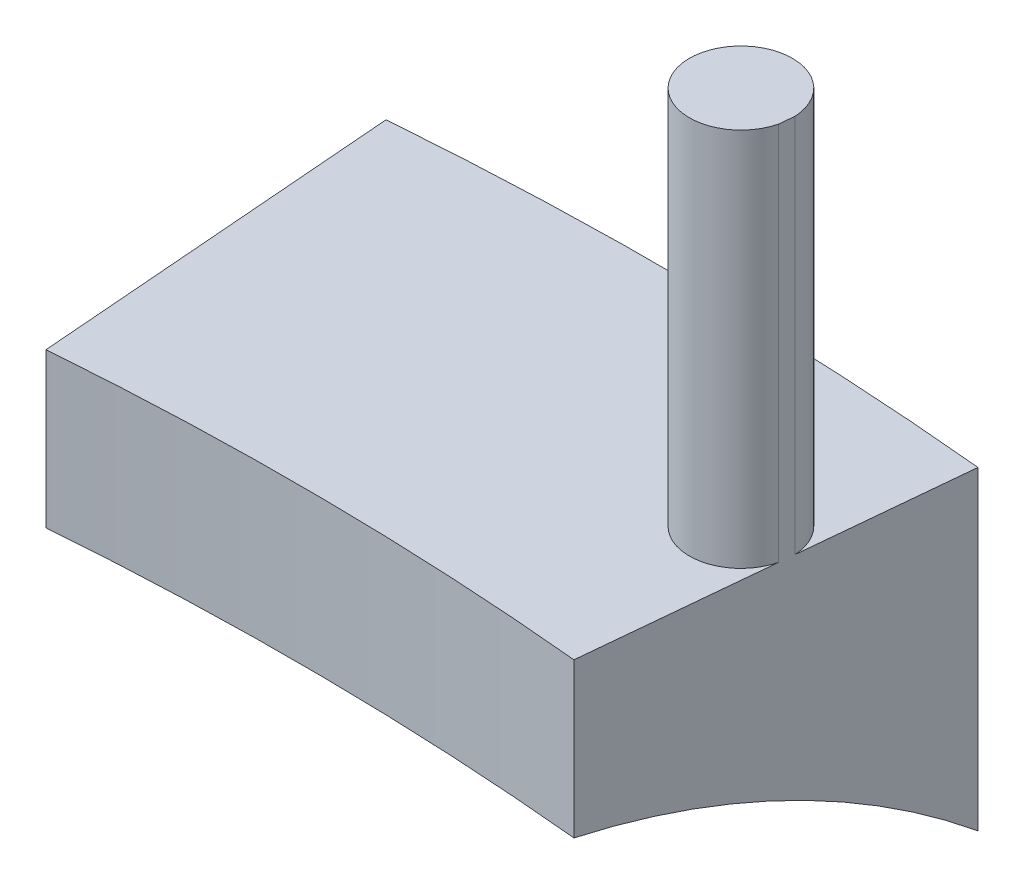
SolidWorks part; units mm, degrees
ref_plane "Front Plane" through (0, 0, 0) normal (0, 0, 1) x (1, 0, 0)
ref_plane "Top Plane" through (0, 0, 0) normal (0, 1, 0) x (1, 0, 0)
ref_plane "Right Plane" through (0, 0, 0) normal (1, 0, 0) x (0, 0, -1)
sketch "Sketch1" plane through (0, 0, 0) normal (0, 1, 0) x (1, 0, 0)
  circle A0 centre (0, 0) radius 140.97
  circle A1 centre (0, 0) radius 125.73
  dimension "D1" = 281.94
  dimension "D2" = 251.46
extrude "Boss-Extrude1" add sketch "Sketch1" along normal blind 12.954
sketch "Sketch3" plane through (0, 12.954, 0) normal (0, 1, 0) x (1, 0, 0)
  line L0 (0, 0) -> (13.4916, 140.3229)
  line L1 (13.4916, 140.3229) -> (0, 0)
  line L2 (0, 0) -> (-11.0802, 140.5339)
  circle A0 centre (0, 0) radius 140.97 construction
  circle A1 centre (0, 0) radius 140.97
  circle M3 centre (0, 0) radius 140.97
  circle M4 centre (0, 0) radius 125.73
  dimension "D1" = 10
extrude "Cut-Extrude1" cut sketch "Sketch3" against normal blind 12.954 contours L0 L2 M4 | L2 L0 M4 M3
sketch "Sketch5" plane through (0, 0, 0) normal (0, 1, 0) x (1, 0, 0)
  line L0 (-9.8823, 125.341) -> (-11.0802, 140.5339) construction
  line L1 (12.033, 125.1529) -> (13.4916, 140.3229) construction
  arc A1 (-10.4813, 132.9374) -> (12.7623, 132.7379) centre (0, 0) cw
  circle A2 centre (10.7123, 133.3451) radius 2.1209
  dimension "D1" = 4.2418
  dimension "D2" = 2.05
  dimension "D3" = 133.35
extrude "Boss-Extrude2" add sketch "Sketch5" along normal blind 28.575 contours A2
sketch "Sketch2" plane through (0, 0, 0) normal (0, 0, 1) x (1, 0, 0)
  line L0 (0, 12.954) -> (-125.73, 12.954)
  line L1 (13.4916, 12.954) -> (-11.0802, 12.954) construction
  line L2 (-125.73, 12.954) -> (-125.73, 6.604)
  line L3 (-125.73, 6.604) -> (-125.73, 0)
  line L4 (-125.73, 0) -> (-140.97, 0)
  line L5 (0, 0) -> (0, 30.8515)
  arc A0 (-125.73, 6.604) -> (-140.97, 0) centre (-121.1655, -24.8162) ccw
  dimension "D3" = 31.75
  dimension "D1" = 125.73
  dimension "D2" = 6.35
revolve "Cut-Revolve1" cut sketch "Sketch2" angle 360 about L5
sketch "Sketch6" plane through (0, 0, 0) normal (0.9954, 0, 0.0957) x (0.0957, 0, -0.9954)
  line L1 (114.9487, -1.4366) -> (150.8904, -1.4366)
  line L2 (114.9487, -1.4366) -> (114.9487, 48.5634)
  line L3 (114.9487, 48.5634) -> (150.8904, 48.5634)
  line L4 (150.8904, -1.4366) -> (150.8904, 48.5634)
  dimension "D1" = 50
extrude "Cut-Extrude2" cut sketch "Sketch6" along normal blind 25.4
